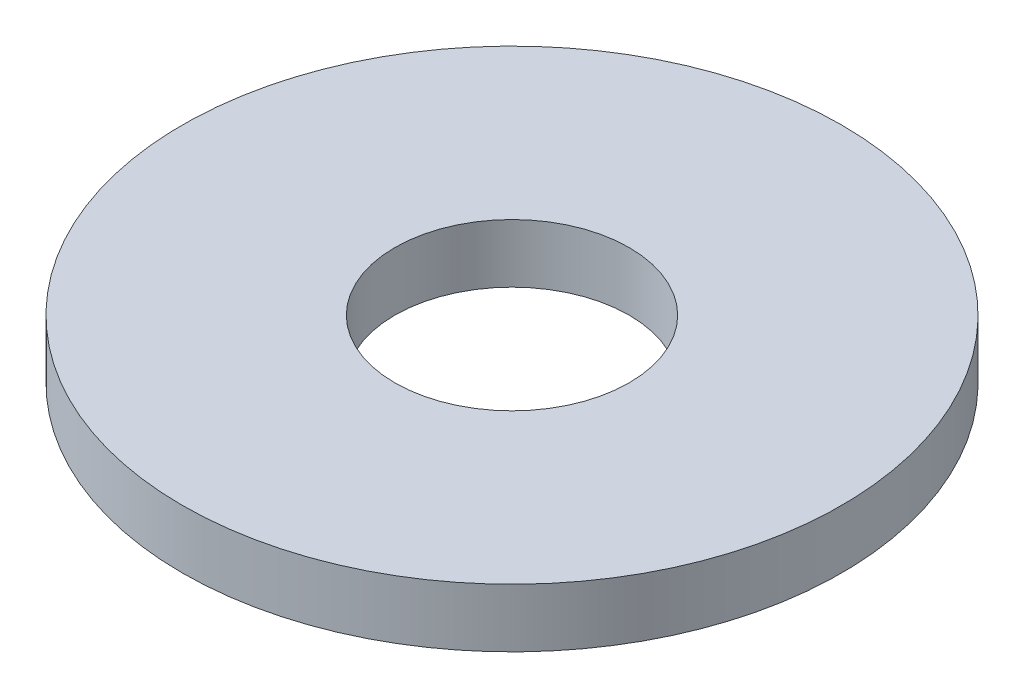
SolidWorks part; units mm, degrees
ref_plane "Front Plane" through (0, 0, 0) normal (0, 0, 1) x (1, 0, 0)
ref_plane "Top Plane" through (0, 0, 0) normal (0, 1, 0) x (1, 0, 0)
ref_plane "Right Plane" through (0, 0, 0) normal (1, 0, 0) x (0, 0, -1)
sketch "Sketch1" plane through (0, 0, 0) normal (0, 1, 0) x (1, 0, 0)
  circle A0 centre (0, 0) radius 3.2
  circle A1 centre (0, 0) radius 9
  dimension "D1" = 6.4
  dimension "D2" = 18
extrude "Boss-Extrude1" add sketch "Sketch1" along normal blind 1.6
